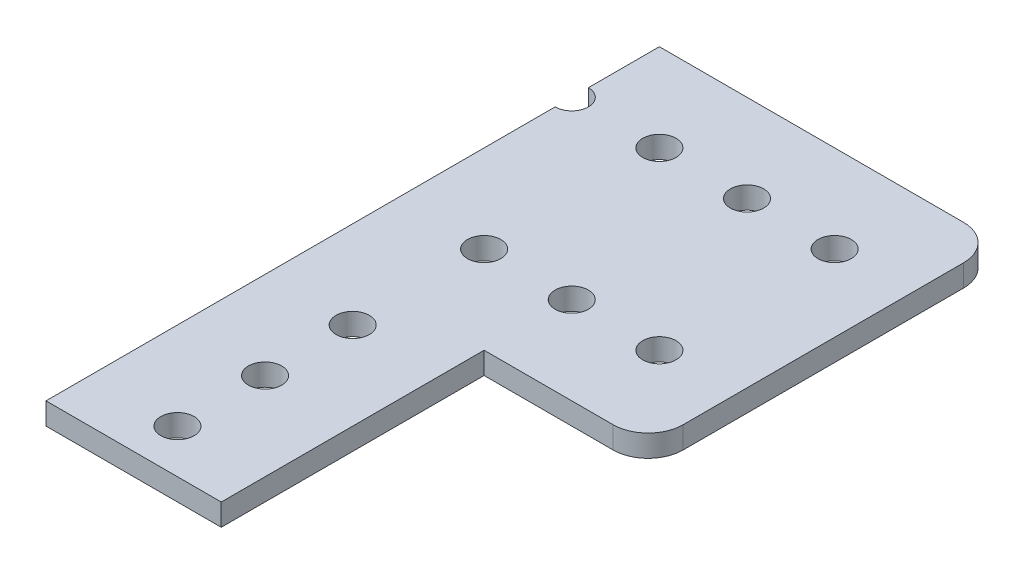
SolidWorks part; units mm, degrees
ref_plane "Front Plane" through (0, 0, 0) normal (0, 0, 1) x (1, 0, 0)
ref_plane "Top Plane" through (0, 0, 0) normal (0, 1, 0) x (1, 0, 0)
ref_plane "Right Plane" through (0, 0, 0) normal (1, 0, 0) x (0, 0, -1)
sketch "Sketch1" plane through (0, 0, 0) normal (0, 1, 0) x (1, 0, 0)
  line L0 (25.4, 50.8) -> (49.1706, 50.8)
  line L1 (0, 0) -> (25.4, 0)
  line L2 (0, 0) -> (0, 50.8)
  line L4 (25.4, 0) -> (25.4, 50.8)
  line L5 (-27.0294, 50.8) -> (0, 50.8)
  line L6 (-27.0294, 50.8) -> (-27.0294, 101.6)
  line L7 (-27.0294, 101.6) -> (49.1706, 101.6)
  line L8 (49.1706, 50.8) -> (49.1706, 101.6)
  dimension "D1" = 101.6
  dimension "D2" = 76.2
  dimension "D3" = 50.8
  dimension "D4" = 25.4
extrude "Boss-Extrude1" add sketch "Sketch1" along normal blind 3.175
fillet "Fillet1" radius 5.08 6 edges at (-27.0294, 1.5875, -50.8) (0, 1.5875, 0) (25.4, 1.5875, 0) (49.1706, 1.5875, -50.8) (49.1706, 1.5875, -101.6) (-27.0294, 1.5875, -101.6)
sketch "Sketch2" plane through (0, 3.175, 0) normal (0, 1, 0) x (1, 0, 0)
  line L0 (0, 12.7) -> (25.4, 12.7)
  line L1 (0, 50.8) -> (0, 5.08) construction
  line L2 (25.4, 5.08) -> (25.4, 50.8) construction
  line L3 (25.4, 12.7) -> (25.4, 0)
  line L4 (25.4, 0) -> (0, 0)
  line L5 (0, 0) -> (0, 12.7)
  line L8 (-27.0294, 96.52) -> (-27.0294, 55.88) construction
  line L9 (-247.65, 101.6) -> (196.85, 101.6) construction
  circle A0 centre (12.7, 19.05) radius 2.413
  circle A1 centre (12.7, 31.75) radius 2.413
  circle A2 centre (12.7, 44.45) radius 2.413
  circle A3 centre (-12.6988, 88.9) radius 2.413
  circle A4 centre (0.0012, 88.9) radius 2.413
  circle A5 centre (12.7012, 88.9) radius 2.413
  circle A6 centre (25.4012, 88.9) radius 2.413
  circle A7 centre (38.1012, 88.9) radius 2.413
  circle A11 centre (12.7012, 63.5) radius 2.413
  circle A12 centre (25.4012, 63.5) radius 2.413
  circle A13 centre (38.1012, 63.5) radius 2.413
  dimension "D2" = 4.826
  dimension "D3" = 6.35
  dimension "D6" = 4.826
  dimension "D7" = 14.3307
  dimension "D8" = 12.7
  dimension "D11" = 12.7
  dimension "D12" = 25.4
  dimension "D1" = 12.7
  dimension "D4" = 12.7
  dimension "D5" = 3
  dimension "D9" = 5
  dimension "D10" = 2
extrude "Cut-Extrude1" cut sketch "Sketch2" against normal through all
sketch "Sketch3" plane through (0, 3.175, 0) normal (0, 1, 0) x (1, 0, 0)
  line L1 (0, 50.8) -> (-27.94, 50.8)
  line L2 (0, 50.8) -> (0, 101.6)
  line L3 (0, 101.6) -> (-27.94, 101.6)
  line L4 (-27.94, 50.8) -> (-27.94, 101.6)
  dimension "D1" = 50.8
  dimension "D2" = 27.94
extrude "Cut-Extrude2" cut sketch "Sketch3" against normal through all
